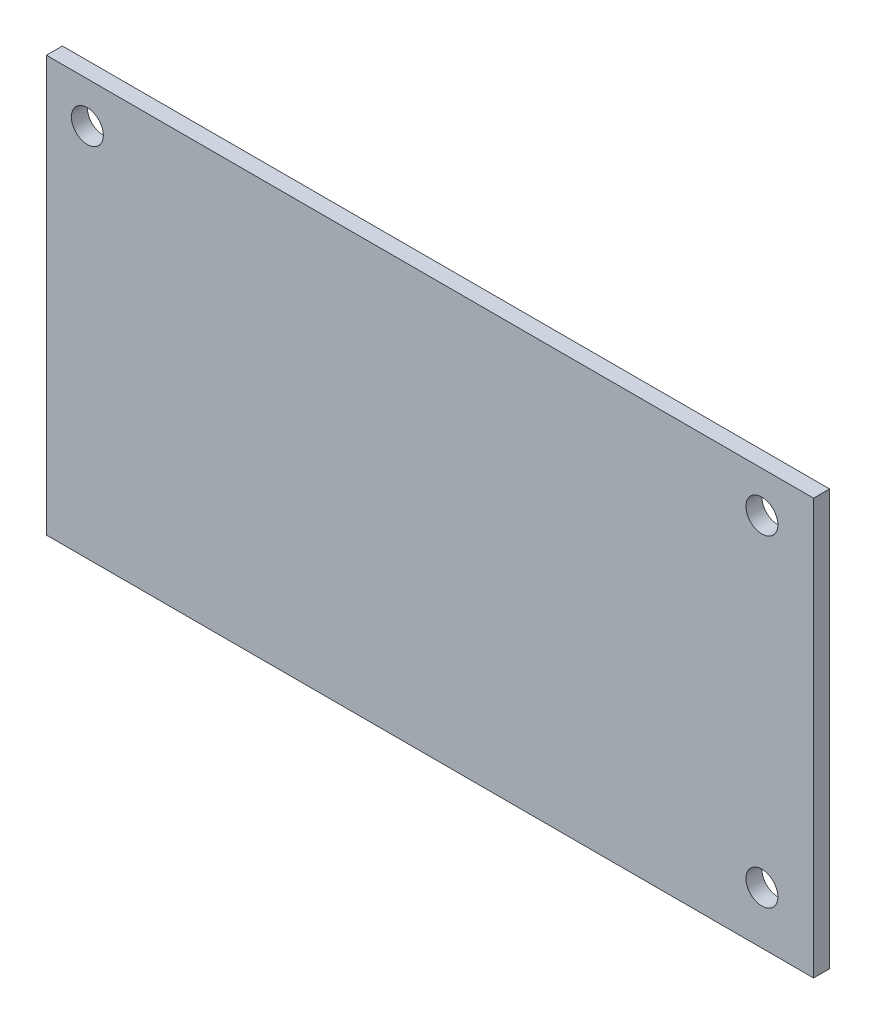
SolidWorks part; units mm, degrees
ref_plane "Front Plane" through (0, 0, 0) normal (0, 0, 1) x (1, 0, 0)
ref_plane "Top Plane" through (0, 0, 0) normal (0, 1, 0) x (1, 0, 0)
ref_plane "Right Plane" through (0, 0, 0) normal (1, 0, 0) x (0, 0, -1)
sketch "Sketch1" plane through (0, 0, 0) normal (0, 0, 1) x (1, 0, 0)
  line L0 (0, 0) -> (76.2, 0)
  line L1 (0, 0) -> (0, 41.275)
  line L2 (76.2, 0) -> (76.2, 41.275)
  line L3 (0, 41.275) -> (76.2, 41.275)
  circle A0 centre (4.064, 37.211) radius 1.5875
  circle A1 centre (71.064, 37.211) radius 1.5875
  circle A2 centre (71.064, 5.207) radius 1.5875
  dimension "D3" = 4.064
  dimension "D7" = 3.175
  dimension "D1" = 76.2
  dimension "D2" = 41.275
  dimension "D4" = 4.064
  dimension "D5" = 67
  dimension "D6" = 32.004
extrude "Boss-Extrude1" add sketch "Sketch1" along normal blind 1.5875
sketch "Sketch2" plane through (0, 0, 1.5875) normal (0, 0, 1) x (1, 0, 0)
  line L0 (30.48, 36.195) -> (40.64, 36.195)
  line L1 (30.48, 36.195) -> (30.48, 38.735)
  line L2 (40.64, 36.195) -> (40.64, 38.735)
  line L3 (30.48, 38.735) -> (40.64, 38.735)
  line L4 (43.18, 36.195) -> (50.8, 36.195)
  line L5 (43.18, 36.195) -> (43.18, 38.735)
  line L6 (50.8, 36.195) -> (50.8, 38.735)
  line L7 (43.18, 38.735) -> (50.8, 38.735)
  line L8 (0, 41.275) -> (0, 0) construction
  line L9 (3.175, 19.05) -> (6.35, 19.05)
  line L10 (3.175, 19.05) -> (3.175, 15.875)
  line L11 (3.175, 15.875) -> (6.35, 15.875)
  line L12 (6.35, 19.05) -> (6.35, 15.875)
  line L13 (6.35, 15.875) -> (3.175, 15.875)
  line L14 (6.35, 15.875) -> (6.35, 12.7)
  line L15 (6.35, 12.7) -> (3.175, 12.7)
  line L16 (3.175, 15.875) -> (3.175, 12.7)
  line L17 (3.175, 12.7) -> (6.35, 12.7)
  line L18 (3.175, 12.7) -> (3.175, 9.525)
  line L19 (3.175, 9.525) -> (6.35, 9.525)
  line L20 (6.35, 12.7) -> (6.35, 9.525)
  line L21 (6.35, 9.525) -> (3.175, 9.525)
  line L22 (6.35, 9.525) -> (6.35, 6.35)
  line L23 (6.35, 6.35) -> (3.175, 6.35)
  line L24 (3.175, 9.525) -> (3.175, 6.35)
  line L25 (0, 0) -> (76.2, 0) construction
  line L26 (76.2, 0) -> (76.2, 41.275) construction
  line L27 (76.2, 41.275) -> (0, 41.275) construction
  point P27 (38.1, 41.275)
  dimension "D1" = 3.175
  dimension "D2" = 6.35
  dimension "D3" = 3.175
  dimension "D4" = 10.16
  dimension "D5" = 7.62
  dimension "D6" = 2.54
  dimension "D7" = 25.4
  dimension "D8" = 2.54
  dimension "D9" = 2.54
